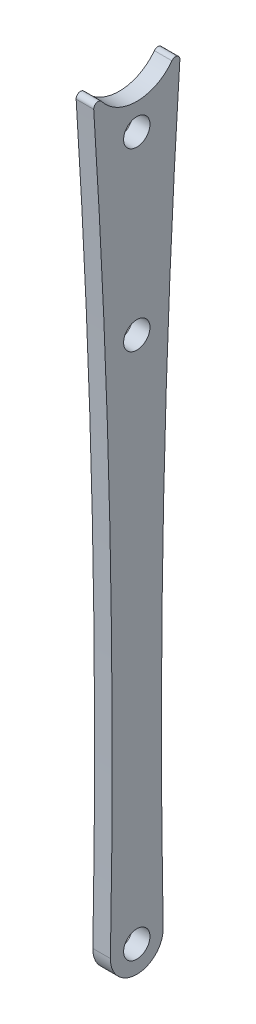
SolidWorks part; units mm, degrees
ref_plane "前视基准面" through (0, 0, 0) normal (0, 0, 1) x (1, 0, 0)
ref_plane "上视基准面" through (0, 0, 0) normal (0, 1, 0) x (1, 0, 0)
ref_plane "右视基准面" through (0, 0, 0) normal (1, 0, 0) x (0, 0, -1)
sketch "草图1" plane through (0, 0, 0) normal (1, 0, 0) x (0, 0, -1)
  line L0 (0, 0) -> (0, 49.3906) construction
  circle A0 centre (0, 0) radius 1.5
  arc A1 (-2.9994, 0.0596) -> (2.9994, 0.0596) centre (0, 0) ccw
  arc A2 (2.9994, 0.0596) -> (4.899, 84.6676) centre (1002.8018, 19.9383) cw
  arc A3 (4.899, 84.6676) -> (4, 85) centre (4.4, 84.7) ccw
  arc A4 (4, 85) -> (-4, 85) centre (0, 88) cw
  arc A5 (-4.899, 84.6676) -> (-4, 85) centre (-4.4, 84.7) cw
  arc A6 (-2.9994, 0.0596) -> (-4.899, 84.6676) centre (-1002.8018, 19.9383) ccw
  circle A7 centre (0, 80) radius 1.5
  circle A8 centre (0, 60) radius 1.5
  dimension "D1" = 1000
  dimension "D2" = 5
  dimension "D3" = 0.5
  dimension "D5" = 20
  dimension "D6" = 80
  dimension "D7" = 3
  dimension "D8" = 3
  dimension "D9" = 8
  dimension "D4" = 4
extrude "凸台-拉伸1" add sketch "草图1" along normal blind 2
move or copy body "实体-移动/复制1" [suppressed] bodies to move or copy 106
move or copy body "实体-移动/复制2" [suppressed] bodies to move or copy 107 parameters "D1"=0, "D2"=0, "D3"=0
move or copy body "实体-移动/复制3" [suppressed] bodies to move or copy 108 parameters "D1"=0, "D2"=0, "D3"=0
